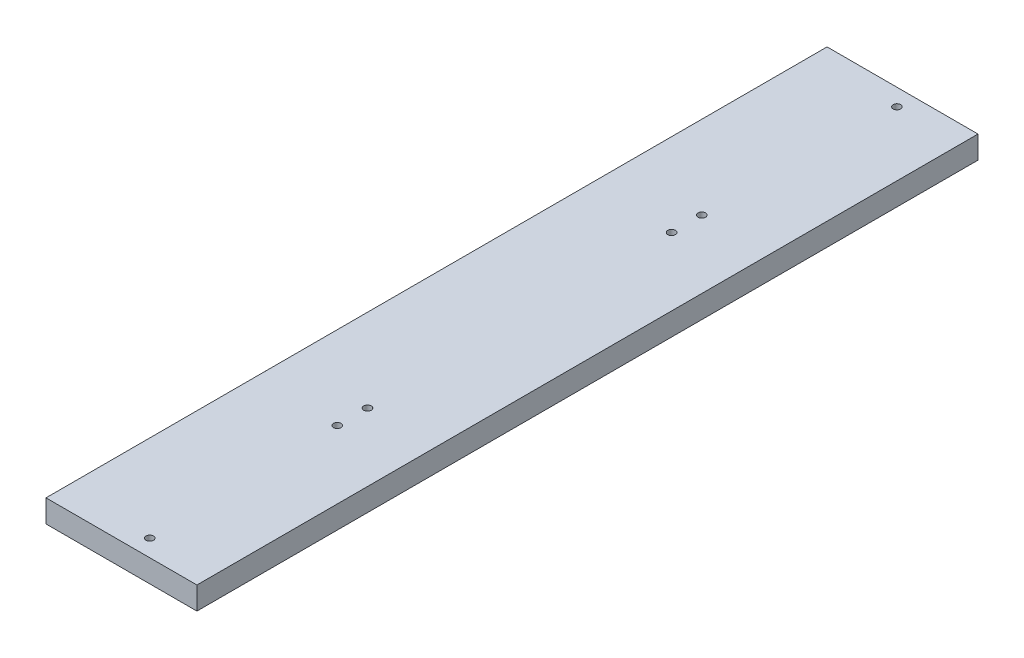
SolidWorks part; units mm, degrees
material "Pine"
ref_plane "Front Plane" through (0, 0, 0) normal (0, 0, 1) x (1, 0, 0)
ref_plane "Top Plane" through (0, 0, 0) normal (0, 1, 0) x (1, 0, 0)
ref_plane "Right Plane" through (0, 0, 0) normal (1, 0, 0) x (0, 0, -1)
sketch "Sketch1" plane through (0, 0, 0) normal (0, 1, 0) x (1, 0, 0)
  line L1 (0, 0) -> (127, 0)
  line L2 (0, 0) -> (0, -657.225)
  line L3 (0, -657.225) -> (127, -657.225)
  line L4 (127, 0) -> (127, -657.225)
  dimension "D1" = 127
  dimension "D2" = 657.225
extrude "Boss-Extrude1" add sketch "Sketch1" along normal blind 19.05
hole_wizard "1/4 (0.25) Diameter Hole1" positions "Sketch3" profile "Sketch2" hole size "1/4" standard "ANSI Inch" end condition up to next
sketch "Sketch3" plane through (0, 0, 0) normal (0, -1, 0) x (-1, 0, 0)
  point P0 (-73.025, -14.2875)
  point P3 (-69.85, -175.26)
  point P6 (-69.85, -200.66)
  point P9 (-69.85, -456.565)
  point P12 (-69.85, -481.965)
  point P15 (-73.025, -642.9375)
sketch "Sketch2" plane through (73.025, 0, 14.2875) normal (1, 0, 0) x (0, 0, -1)
  line L0 (0, 0) -> (0, 19.05)
  line L1 (0, 19.05) -> (3.175, 19.05)
  line L2 (3.175, 19.05) -> (3.175, 0)
  line L5 (3.175, 0) -> (0, 0)
  line L11 (0, -6.35) -> (0, 107.95) construction
  dimension "Thru Hole Dia." = 6.35
  dimension "Thru Hole Depth" = 19.05
